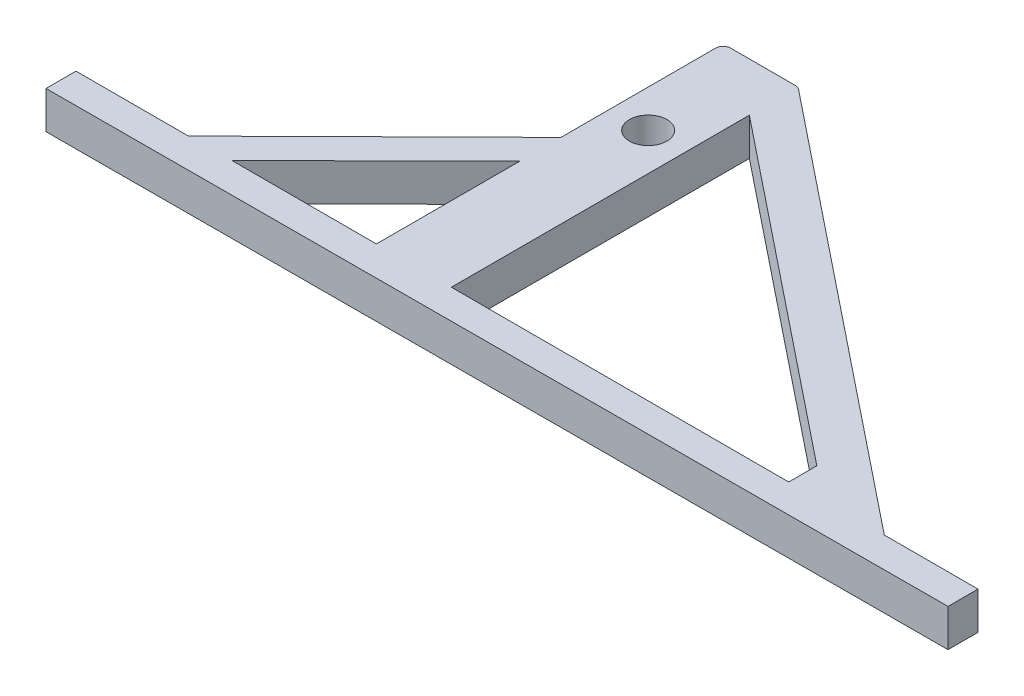
SolidWorks part; units mm, degrees
ref_plane "Front Plane" through (0, 0, 0) normal (0, 0, 1) x (1, 0, 0)
ref_plane "Top Plane" through (0, 0, 0) normal (0, 1, 0) x (1, 0, 0)
ref_plane "Right Plane" through (0, 0, 0) normal (1, 0, 0) x (0, 0, -1)
sketch "Sketch1" plane through (0, 0, 0) normal (0, 1, 0) x (1, 0, 0)
  line L1 (0, 9.525) -> (0, 58.085)
  line L2 (25.4, 9.525) -> (25.4, 110.49)
  line L4 (139.7, 9.525) -> (139.7, 19.05)
  line L6 (171.45, 10.16) -> (26.0957, 126.4434)
  line L7 (139.7, 19.05) -> (25.4, 110.49)
  line L8 (-48.962, 9.525) -> (0, 58.085)
  line L10 (-63.5, 9.3329) -> (0, 72.055)
  line L11 (0, 72.055) -> (0, 124.46)
  line L12 (-63.5, 9.3329) -> (-101.6, 9.3329)
  line L13 (-101.6, 9.3329) -> (-101.6, -0.8271)
  line L15 (2.54, 127) -> (24.509, 127)
  line L17 (203.2, 0) -> (203.2, 10.16)
  line L18 (203.2, 10.16) -> (171.45, 10.16)
  line L20 (139.7, 9.525) -> (25.4, 9.525)
  line L21 (0, 9.525) -> (-48.962, 9.525)
  line L22 (-101.6, -0.8271) -> (203.2, 0)
  circle A0 centre (12.7, 88.9) radius 6.35
  arc A2 (26.0957, 126.4434) -> (24.509, 127) centre (24.509, 124.46) ccw
  arc A3 (0, 124.46) -> (2.54, 127) centre (2.54, 124.46) cw
  point P3 (26.1668, 200.9321)
  point P20 (25.4, 127)
  point P24 (0, 127)
  dimension "D4" = 12.7
  dimension "D7" = 2.54
  dimension "D6" = 12.7
  dimension "D8" = 304.8
  dimension "D9" = 10.16
  dimension "D12" = 10.16
  dimension "D14" = 13.97
  dimension "D15" = 38.1
extrude "Boss-Extrude1" add sketch "Sketch1" along normal blind 12.7
